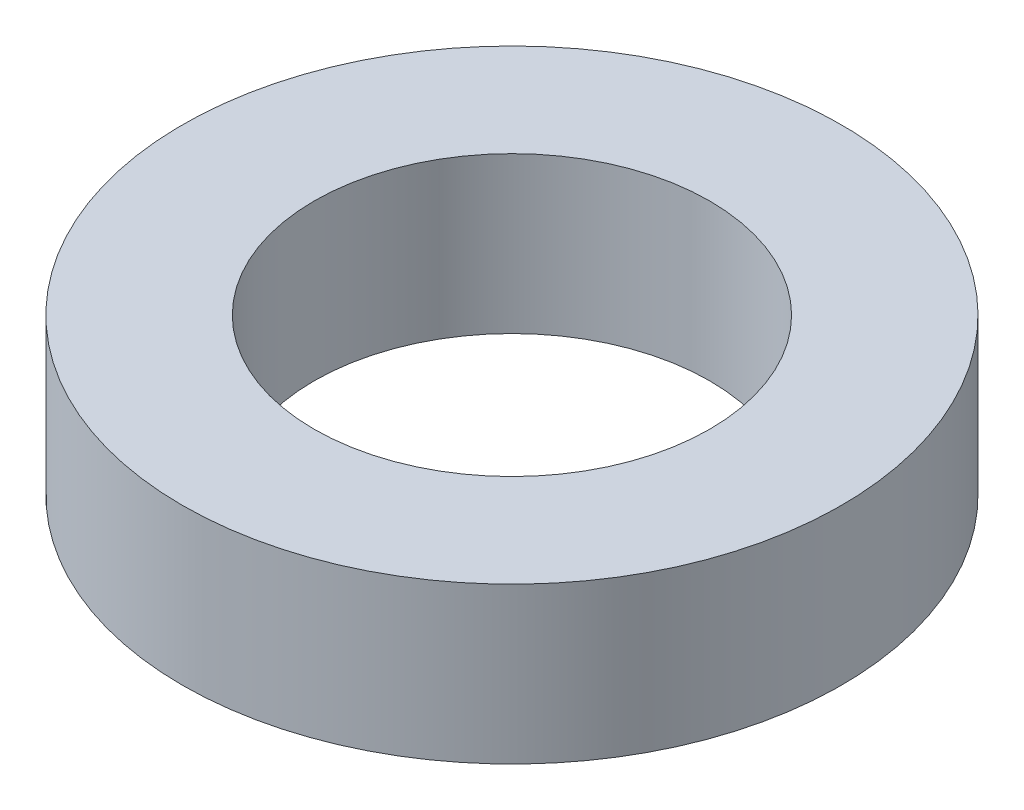
SolidWorks part; units mm, degrees
ref_plane "Front Plane" through (0, 0, 0) normal (0, 0, 1) x (1, 0, 0)
ref_plane "Top Plane" through (0, 0, 0) normal (0, 1, 0) x (1, 0, 0)
ref_plane "Right Plane" through (0, 0, 0) normal (1, 0, 0) x (0, 0, -1)
sketch "Sketch1" plane through (0, 0, 0) normal (0, 1, 0) x (1, 0, 0)
  circle A0 centre (0, 0) radius 2.75
  circle A1 centre (0, 0) radius 1.65
  dimension "D1" = 5.5
  dimension "D2" = 3.3
extrude "Boss-Extrude1" add sketch "Sketch1" along normal blind 1.3 contours A0
sketch "Sketch2" plane through (0, 0, 0) normal (0, -1, 0) x (1, 0, 0)
  circle A0 centre (0, 0) radius 1.65
  dimension "D1" = 3.3
extrude "Cut-Extrude1" cut sketch "Sketch2" against normal blind 1.3
